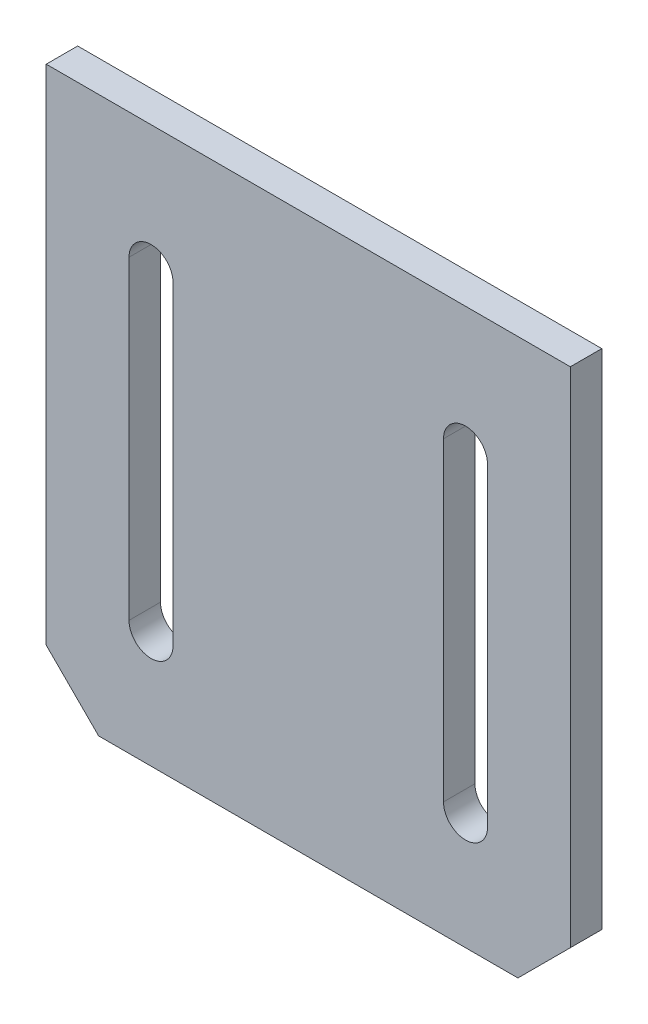
SolidWorks part; units mm, degrees
ref_plane "Plano frontal" through (0, 0, 0) normal (0, 0, 1) x (1, 0, 0)
ref_plane "Plano superior" through (0, 0, 0) normal (0, 1, 0) x (1, 0, 0)
ref_plane "Plano direito" through (0, 0, 0) normal (1, 0, 0) x (0, 0, -1)
sketch "Esboço1" plane through (0, 0, 0) normal (0, 0, 1) x (1, 0, 0)
  line L0 (-25, -21.5) -> (-25, 26.5)
  line L1 (-20, -26.5) -> (20, -26.5)
  line L2 (-25, 26.5) -> (25, 26.5)
  line L3 (25, -21.5) -> (25, 26.5)
  line L4 (-25, -26.5) -> (25, 26.5) construction
  line L5 (-25, 26.5) -> (25, -26.5) construction
  line L6 (0, -26.5) -> (0, 45.1477) construction
  line L7 (15, 14.5) -> (15, -15.5) construction
  line L8 (17.1, 14.5) -> (17.1, -15.5)
  line L9 (12.9, 14.5) -> (12.9, -15.5)
  line L10 (-15, 14.5) -> (-15, -15.5) construction
  line L11 (-17.1, 14.5) -> (-17.1, -15.5)
  line L12 (-12.9, 14.5) -> (-12.9, -15.5)
  line L13 (-20, -26.5) -> (-25, -21.5)
  line L14 (20, -26.5) -> (25, -21.5)
  arc A0 (17.1, 14.5) -> (12.9, 14.5) centre (15, 14.5) ccw
  arc A1 (12.9, -15.5) -> (17.1, -15.5) centre (15, -15.5) ccw
  arc A2 (-17.1, 14.5) -> (-12.9, 14.5) centre (-15, 14.5) cw
  arc A3 (-12.9, -15.5) -> (-17.1, -15.5) centre (-15, -15.5) cw
  point P1 (0, 0)
  point P10 (15, -0.5)
  point P17 (-15, -0.5)
  point P22 (0, 0)
  dimension "D1" = 50
  dimension "D2" = 53
  dimension "D3" = 30
  dimension "D4" = 11
  dimension "D5" = 30
  dimension "D6" = 4.2
  dimension "D7" = 5
  dimension "D8" = 45
  dimension "D9" = 5
  dimension "D10" = 45
extrude "Ressalto-extrusão1" add sketch "Esboço1" along normal blind 3
